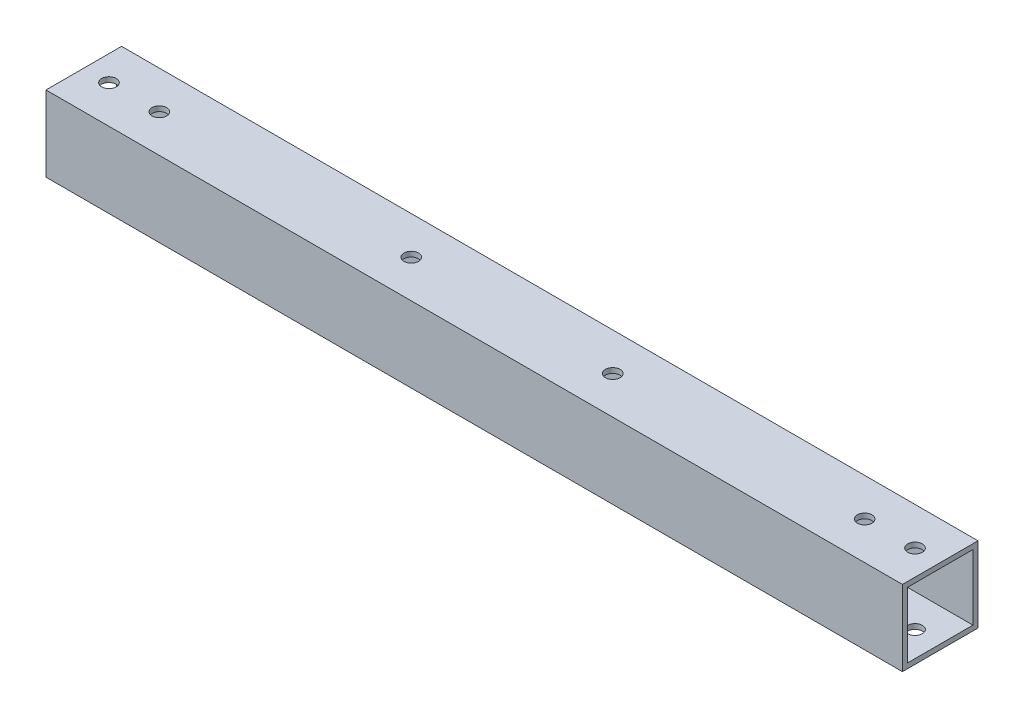
SolidWorks part; units mm, degrees
material "Thornel Mat VMA"
ref_plane "前视基准面" through (0, 0, 0) normal (0, 0, 1) x (1, 0, 0)
ref_plane "上视基准面" through (0, 0, 0) normal (0, 1, 0) x (1, 0, 0)
ref_plane "右视基准面" through (0, 0, 0) normal (1, 0, 0) x (0, 0, -1)
other "Configuration Table"
sketch "草图1" plane through (0, 0, 0) normal (0, 1, 0) x (1, 0, 0)
  line L0 (-85, 0) -> (85, 0)
  dimension "D1" = 170
other "铝管 15X15X1(1)"
ref_plane "基准面1" through (-85, 0, 0) normal (1, 0, 0) x (0, 0, -1)
sketch "草图11" plane through (-85, 0, 0) normal (1, 0, 0) x (0, 0, -1)
  line L1 (-7.5, -7.5) -> (7.5, -7.5)
  line L2 (-7.5, -7.5) -> (-7.5, 7.5)
  line L3 (-7.5, 7.5) -> (7.5, 7.5)
  line L4 (7.5, -7.5) -> (7.5, 7.5)
  line L5 (-7.5, -7.5) -> (7.5, 7.5) construction
  line L6 (-7.5, 7.5) -> (7.5, -7.5) construction
  line L7 (-6.5, -6.5) -> (6.5, -6.5)
  line L8 (-6.5, -6.5) -> (-6.5, 6.5)
  line L9 (-6.5, 6.5) -> (6.5, 6.5)
  line L10 (6.5, -6.5) -> (6.5, 6.5)
  line L11 (-6.5, -6.5) -> (6.5, 6.5) construction
  line L12 (-6.5, 6.5) -> (6.5, -6.5) construction
  point P0 (0, 0)
  point P6 (0, 0)
  point P11 (0, 0)
  dimension "D1" = 15
  dimension "D2" = 15
  dimension "D3" = 13
  dimension "D4" = 13
sketch "草图13" plane through (0, 7.5, 0) normal (0, 1, 0) x (1, 0, 0)
  line L0 (-85, 0) -> (85, 0) construction
  line L1 (-85, 7.5) -> (-85, -7.5) construction
  line L2 (0, 0) -> (0, -7.5) construction
  line L3 (85, -7.5) -> (-85, -7.5) construction
  circle A0 centre (-80, 0) radius 1.45
  circle A1 centre (-70, 0) radius 1.45
  circle A3 centre (70, 0) radius 1.45
  circle A4 centre (80, 0) radius 1.45
  dimension "D1" = 2.9
  dimension "D2" = 2.9
  dimension "D3" = 10
  dimension "D4" = 5
extrude "切除-拉伸2" cut sketch "草图13" against normal through all
sketch "草图14" plane through (0, 7.5, 0) normal (0, 1, 0) x (1, 0, 0)
  line L0 (0, 7.5) -> (0, -7.5) construction
  line L1 (85, 7.5) -> (-85, 7.5) construction
  line L2 (85, -7.5) -> (-85, -7.5) construction
  line L3 (-85, 0) -> (85, 0) construction
  circle A0 centre (-20, 0) radius 1.45
  circle A1 centre (20, 0) radius 1.45
  dimension "D1" = 2.9
  dimension "D2" = 2.9
  dimension "D3" = 20
  dimension "D4" = 20
extrude "切除-拉伸3" cut sketch "草图14" against normal through all
